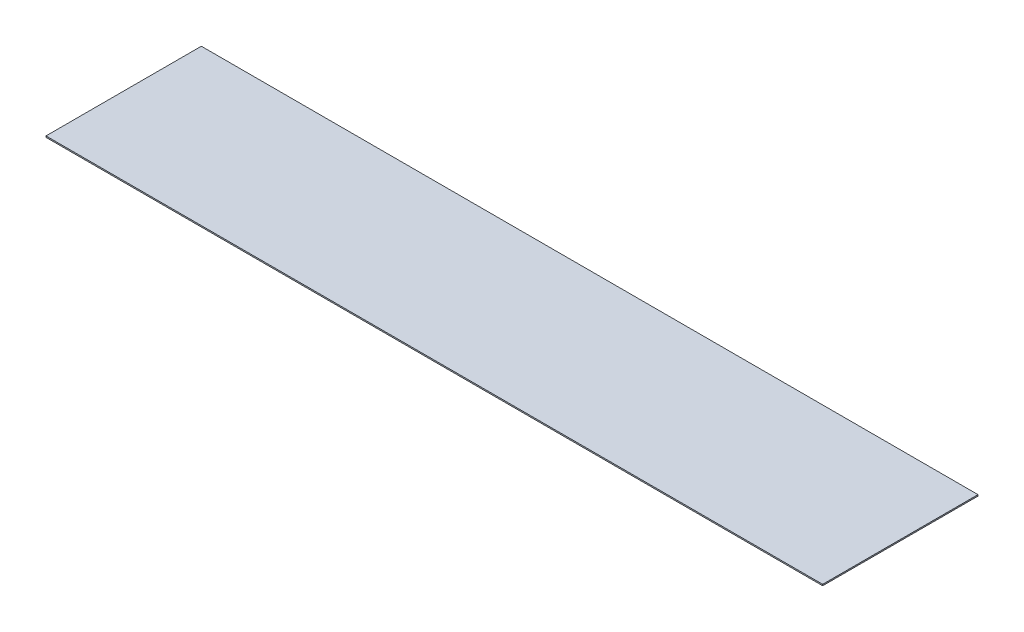
SolidWorks part; units mm, degrees
ref_plane "Front Plane" through (0, 0, 0) normal (0, 0, 1) x (1, 0, 0)
ref_plane "Top Plane" through (0, 0, 0) normal (0, 1, 0) x (1, 0, 0)
ref_plane "Right Plane" through (0, 0, 0) normal (1, 0, 0) x (0, 0, -1)
sketch "Esquisse1" plane through (0, 0, 0) normal (0, 1, 0) x (1, 0, 0)
  line L1 (-3000, 600) -> (3000, 600)
  line L2 (-3000, 600) -> (-3000, -600)
  line L3 (-3000, -600) -> (3000, -600)
  line L4 (3000, 600) -> (3000, -600)
  line L5 (-3000, 600) -> (3000, -600) construction
  line L6 (-3000, -600) -> (3000, 600) construction
  point P0 (0, 0)
extrude "Boss.-Extru.1" add sketch "Esquisse1" along normal blind 10
